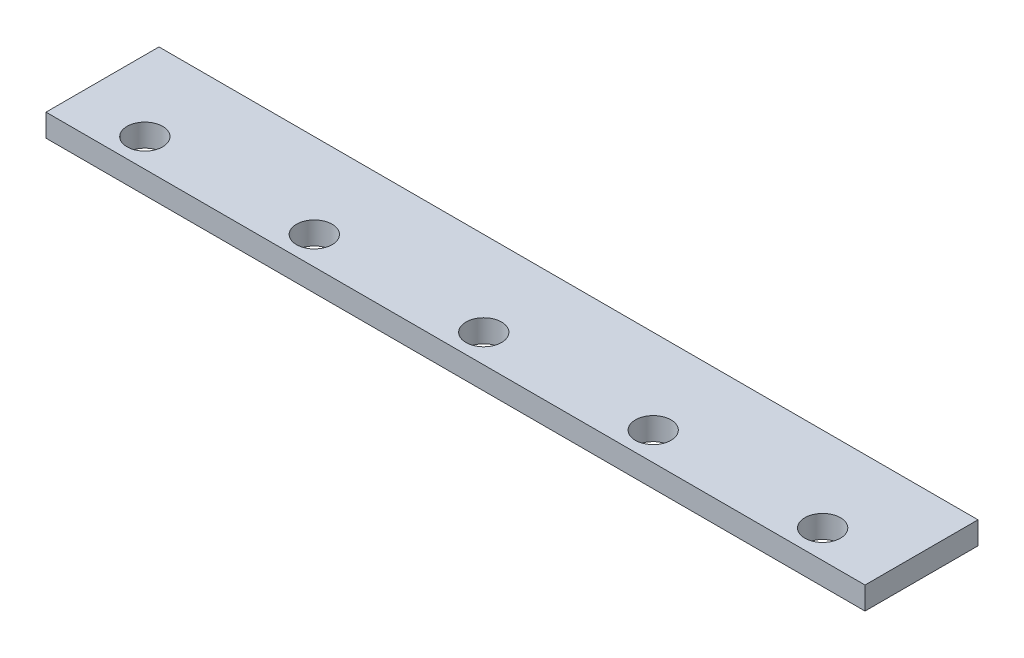
SolidWorks part; units mm, degrees
ref_plane "Front Plane" through (0, 0, 0) normal (0, 0, 1) x (1, 0, 0)
ref_plane "Top Plane" through (0, 0, 0) normal (0, 1, 0) x (1, 0, 0)
ref_plane "Right Plane" through (0, 0, 0) normal (1, 0, 0) x (0, 0, -1)
sketch "Sketch1" plane through (0, 0, 0) normal (0, 1, 0) x (1, 0, 0)
  line L0 (0, 0) -> (580, 0)
  line L1 (0, 0) -> (0, 80)
  line L2 (0, 80) -> (580, 80)
  line L3 (580, 80) -> (580, 0)
  circle A0 centre (50, 20) radius 12.6
  circle A1 centre (530, 20) radius 12.6
  circle A2 centre (410, 20) radius 12.6
  circle A3 centre (290, 20) radius 12.6
  circle A4 centre (170, 20) radius 12.6
  point P6 (50, 20)
  point P16 (0, 0)
  dimension "D1" = 50
  dimension "D2" = 120
  dimension "D3" = 120
  dimension "D4" = 120
  dimension "D5" = 120
  dimension "D8" = 25.2
  dimension "D6" = 20
  dimension "D7" = 80
  dimension "D9" = 580
extrude "Boss-Extrude2" add sketch "Sketch1" along normal blind 16
